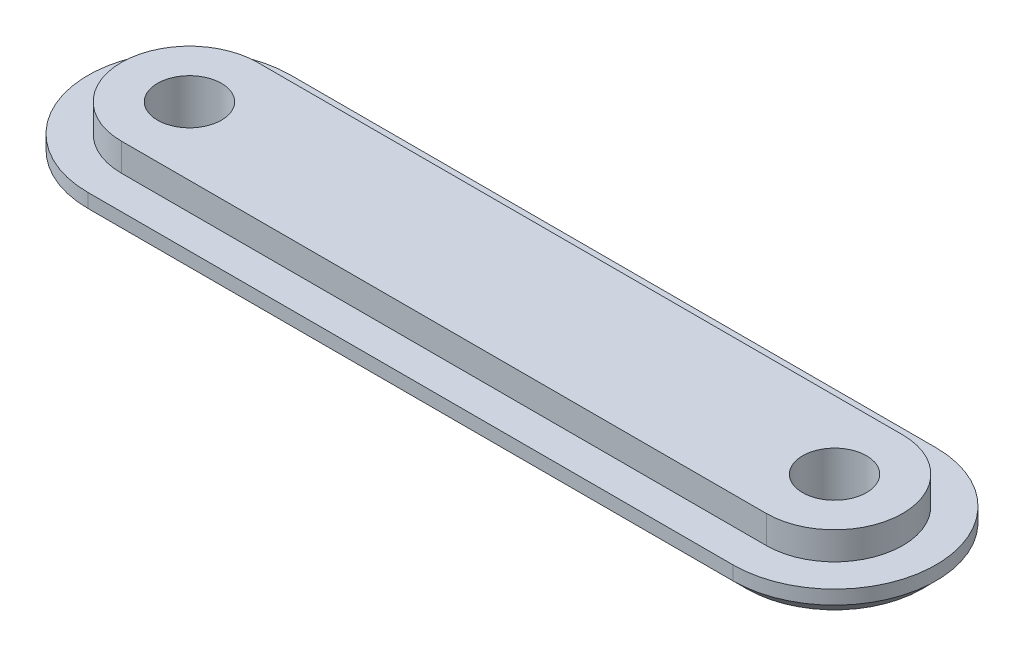
SolidWorks part; units mm, degrees
ref_plane "Front Plane" through (0, 0, 0) normal (0, 0, 1) x (1, 0, 0)
ref_plane "Top Plane" through (0, 0, 0) normal (0, 1, 0) x (1, 0, 0)
ref_plane "Right Plane" through (0, 0, 0) normal (1, 0, 0) x (0, 0, -1)
sketch "Sketch1" plane through (0, 0, 0) normal (0, 1, 0) x (1, 0, 0)
  line L0 (11.6, -2.65) -> (-11.6, -2.65) construction
  line L1 (-11.6, 2.65) -> (11.6, 2.65) construction
  line L2 (11.6, -2.65) -> (-11.6, -2.65) construction
  line L3 (-11.6, 2.65) -> (11.6, 2.65) construction
  line L4 (-11.6, 3.65) -> (11.6, 3.65)
  line L5 (11.6, -3.65) -> (-11.6, -3.65)
  line L6 (-11.6, 2.45) -> (11.6, 2.45)
  line L7 (11.6, -2.45) -> (-11.6, -2.45)
  arc A0 (11.6, -2.65) -> (11.6, 2.65) centre (11.6, 0) ccw construction
  arc A1 (-11.6, 2.65) -> (-11.6, -2.65) centre (-11.6, 0) ccw construction
  arc A2 (11.6, -2.65) -> (11.6, 2.65) centre (11.6, 0) ccw construction
  arc A3 (-11.6, 2.65) -> (-11.6, -2.65) centre (-11.6, 0) ccw construction
  arc A4 (11.6, -3.65) -> (11.6, 3.65) centre (11.6, 0) ccw
  arc A5 (-11.6, 3.65) -> (-11.6, -3.65) centre (-11.6, 0) ccw
  arc A6 (11.6, -2.45) -> (11.6, 2.45) centre (11.6, 0) ccw
  arc A7 (-11.6, 2.45) -> (-11.6, -2.45) centre (-11.6, 0) ccw
  dimension "D1" = 1
  dimension "D2" = 0.2
sketch "Sketch2" plane through (0, 0, 0) normal (0, 1, 0) x (1, 0, 0)
  line L2 (11.6, 3.65) -> (-11.6, 3.65)
  line L3 (-11.6, -3.65) -> (11.6, -3.65)
  line L4 (11.6, 3.65) -> (-11.6, 3.65)
  line L5 (-11.6, -3.65) -> (11.6, -3.65)
  arc A2 (11.6, -3.65) -> (11.6, 3.65) centre (11.6, 0) ccw
  arc A3 (-11.6, 3.65) -> (-11.6, -3.65) centre (-11.6, 0) ccw
  arc A4 (11.6, -3.65) -> (11.6, 3.65) centre (11.6, 0) ccw
  arc A5 (-11.6, 3.65) -> (-11.6, -3.65) centre (-11.6, 0) ccw
  dimension "D1" = 0
extrude "Boss-Extrude1" add sketch "Sketch2" against normal blind 1
sketch "Sketch3" plane through (0, 0, 0) normal (0, 1, 0) x (1, 0, 0)
  line L6 (-11.6, -2.45) -> (11.6, -2.45)
  line L7 (11.6, 2.45) -> (-11.6, 2.45)
  line L8 (-11.6, -2.45) -> (11.6, -2.45)
  line L9 (11.6, 2.45) -> (-11.6, 2.45)
  arc A6 (11.6, -2.45) -> (11.6, 2.45) centre (11.6, 0) ccw
  arc A7 (-11.6, 2.45) -> (-11.6, -2.45) centre (-11.6, 0) ccw
  arc A8 (11.6, -2.45) -> (11.6, 2.45) centre (11.6, 0) ccw
  arc A9 (-11.6, 2.45) -> (-11.6, -2.45) centre (-11.6, 0) ccw
  dimension "D2" = 0
extrude "Boss-Extrude2" add sketch "Sketch3" along normal blind 1
sketch "Sketch4" plane through (0, 1, 0) normal (0, 1, 0) x (1, 0, 0)
  circle A0 centre (-11.6, 0) radius 1.15
  circle A1 centre (11.6, 0) radius 1.15
  dimension "D1" = 2.3
extrude "Cut-Extrude1" cut sketch "Sketch4" against normal through all
chamfer "Chamfer1" distance 0.5 angle 45 4 edges at (0, -1, -3.65) (-15.25, -1, 0) (15.25, -1, 0) (0, -1, 3.65)
